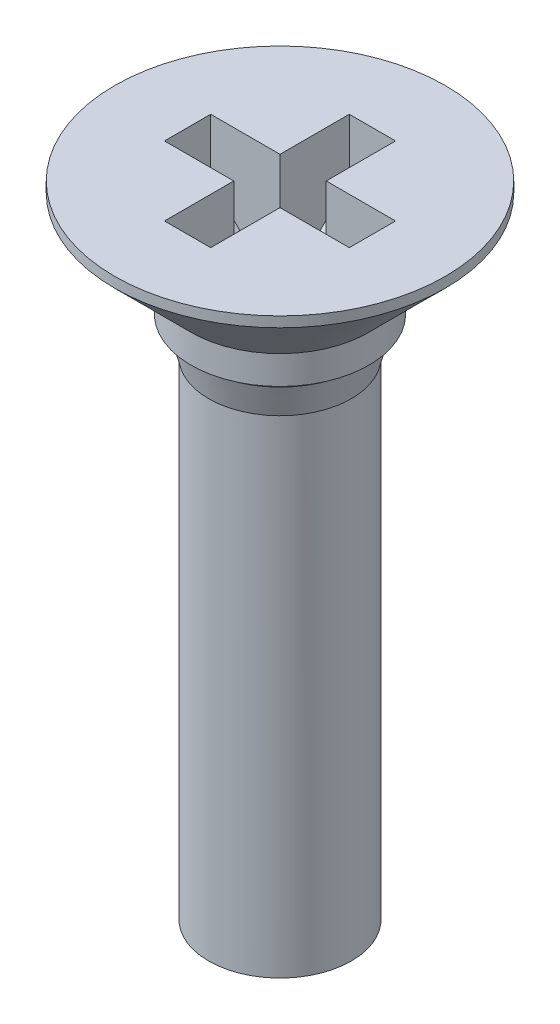
SolidWorks part; units mm, degrees
ref_plane "Vorderseite" through (0, 0, 0) normal (0, 0, 1) x (1, 0, 0)
ref_plane "Oben" through (0, 0, 0) normal (0, 1, 0) x (1, 0, 0)
ref_plane "Rechts" through (0, 0, 0) normal (1, 0, 0) x (0, 0, -1)
sketch "Skizze1" plane through (0, 0, 0) normal (0, 0, 1) x (1, 0, 0)
  line L0 (0, 0) -> (4.65, 0)
  line L1 (4.65, 0) -> (4.65, -0.29)
  line L2 (4.65, -0.29) -> (2.5, -2.44)
  line L3 (2.24, -3.24) -> (2.24, -3.4398)
  line L4 (2.24, -3.4398) -> (2.0095, -4.3)
  line L5 (2.0095, -4.3) -> (2.0095, -16)
  line L6 (2.0095, -16) -> (0, -16)
  line L7 (0, 0) -> (0, -16) construction
  line L8 (0, 0) -> (0, -16)
  line L10 (2.5, -2.44) -> (2.5, -3.24)
  line L12 (2.5, -3.24) -> (2.24, -3.24)
  point P3 (2.24, -2.7)
  dimension "D1" = 45
  dimension "D2" = 15
  dimension "K" = 2.7
  dimension "DA" = 9.3
  dimension "DK" = 4.019
  dimension "L" = 16
  dimension "DG" = 5
  dimension "A" = 1.6
  dimension "DF" = 4.48
  dimension "P" = 0.8
revolve "Basis-Rotation" add sketch "Skizze1" angle 360 about L7
sketch "Skizze2" plane through (0, 0, 0) normal (0, 0, 1) x (1, 0, 0)
  line L0 (0, -3.2) -> (0, 0) construction
  line L1 (0, 0) -> (0, -16) construction
  line L2 (-1, -3.2) -> (1, -3.2)
  line L3 (2.6, 0) -> (2.6, -1.6)
  line L4 (2.6, -1.6) -> (1, -3.2)
  line L5 (2.6, 0) -> (-2.6, 0)
  line L6 (-2.6, -1.6) -> (-1, -3.2)
  line L7 (-2.6, 0) -> (-2.6, -1.6)
  line L8 (0, -1.6) -> (2.6, -1.6) construction
  line L9 (4.65, 0) -> (-4.65, 0) construction
  line L11 (2.5, -2.44) -> (4.65, -0.29) construction
  point P11 (0, 0)
  dimension "M" = 5.2
  dimension "T" = 3.2
extrude "Kreuzschlitz1 H" cut sketch "Skizze2" against normal blind 0.65 and the other way blind 0.65
sketch "Skizze3" plane through (0, 0, 0) normal (1, 0, 0) x (0, 0, -1)
  line L0 (0, -3.2) -> (0, 0) construction
  line L2 (-1, -3.2) -> (1, -3.2)
  line L3 (2.6, 0) -> (2.6, -1.6)
  line L4 (2.6, -1.6) -> (1, -3.2)
  line L5 (2.6, 0) -> (-2.6, 0)
  line L6 (-2.6, -1.6) -> (-1, -3.2)
  line L7 (-2.6, 0) -> (-2.6, -1.6)
  line L8 (0, -1.6) -> (2.6, -1.6) construction
  point P11 (0, 0)
extrude "Kreuzschlitz2 H" cut sketch "Skizze3" against normal blind 0.65 and the other way blind 0.65
sketch "Skizze4" plane through (2.4522, 0, -1.8507) normal (0, 1, 0) x (-1, 0, 0)
  line L0 (7.3522, 1.8507) -> (-2.4478, 1.8507) construction
  line L1 (2.4522, -3.0493) -> (2.4522, 6.7507) construction
  line L2 (-2.4478, 1.0342) -> (-2.4478, 2.6672)
  line L3 (-2.4478, 1.0342) -> (0.0059, 1.0342)
  line L4 (0.0059, 1.0342) -> (0.8191, 0.6258)
  line L5 (1.2273, 0.2176) -> (-1.0126, -1.6141)
  line L6 (0.8191, 0.6258) -> (-1.0126, -1.6141)
  line L7 (1.6357, -0.5956) -> (1.2273, 0.2176)
  line L8 (1.6357, -3.0493) -> (1.6357, -0.5956)
  line L9 (1.6357, -3.0493) -> (3.2687, -3.0493)
  line L10 (3.2687, -3.0493) -> (3.2687, -0.5956)
  line L11 (3.2687, -0.5956) -> (3.6772, 0.2176)
  line L12 (2.4522, 1.8507) -> (-1.0126, -1.6141) construction
  line L13 (4.0854, 0.6258) -> (5.917, -1.6141)
  line L14 (3.6772, 0.2176) -> (5.917, -1.6141)
  line L15 (4.8986, 1.0342) -> (4.0854, 0.6258)
  line L16 (7.3522, 1.0342) -> (4.8986, 1.0342)
  line L17 (7.3522, 1.0342) -> (7.3522, 2.6672)
  line L18 (7.3522, 2.6672) -> (4.8986, 2.6672)
  line L19 (4.8986, 2.6672) -> (4.0854, 3.0757)
  line L20 (3.6772, 3.4839) -> (5.917, 5.3156)
  line L21 (4.0854, 3.0757) -> (5.917, 5.3156)
  line L22 (3.2687, 4.2971) -> (3.6772, 3.4839)
  line L23 (3.2687, 6.7507) -> (3.2687, 4.2971)
  line L24 (1.6357, 6.7507) -> (3.2687, 6.7507)
  line L25 (1.6357, 6.7507) -> (1.6357, 4.2971)
  line L26 (1.6357, 4.2971) -> (1.2273, 3.4839)
  line L27 (0.8191, 3.0757) -> (-1.0126, 5.3156)
  line L28 (1.2273, 3.4839) -> (-1.0126, 5.3156)
  line L29 (0.0059, 2.6672) -> (0.8191, 3.0757)
  line L30 (-2.4478, 2.6672) -> (0.0059, 2.6672)
  circle A0 centre (2.4522, 1.8507) radius 4.9 construction
  circle A1 centre (2.4522, 1.8507) radius 2.0415 construction
  circle A2 centre (2.4522, 1.8507) radius 2.579 construction
  dimension "X2" = 4.083
  dimension "X1" = 5.158
  dimension "M" = 9.8
  dimension "D3" = 5.725
  dimension "X3" = 1.633
sketch "Sketch1" plane through (0, -16, 0) normal (0, -1, 0) x (1, 0, 0)
  circle A0 centre (0, 0) radius 2.0095
  dimension "D1" = 4.019
extrude "Boss-Extrude1" add sketch "Sketch1" along normal blind 2
